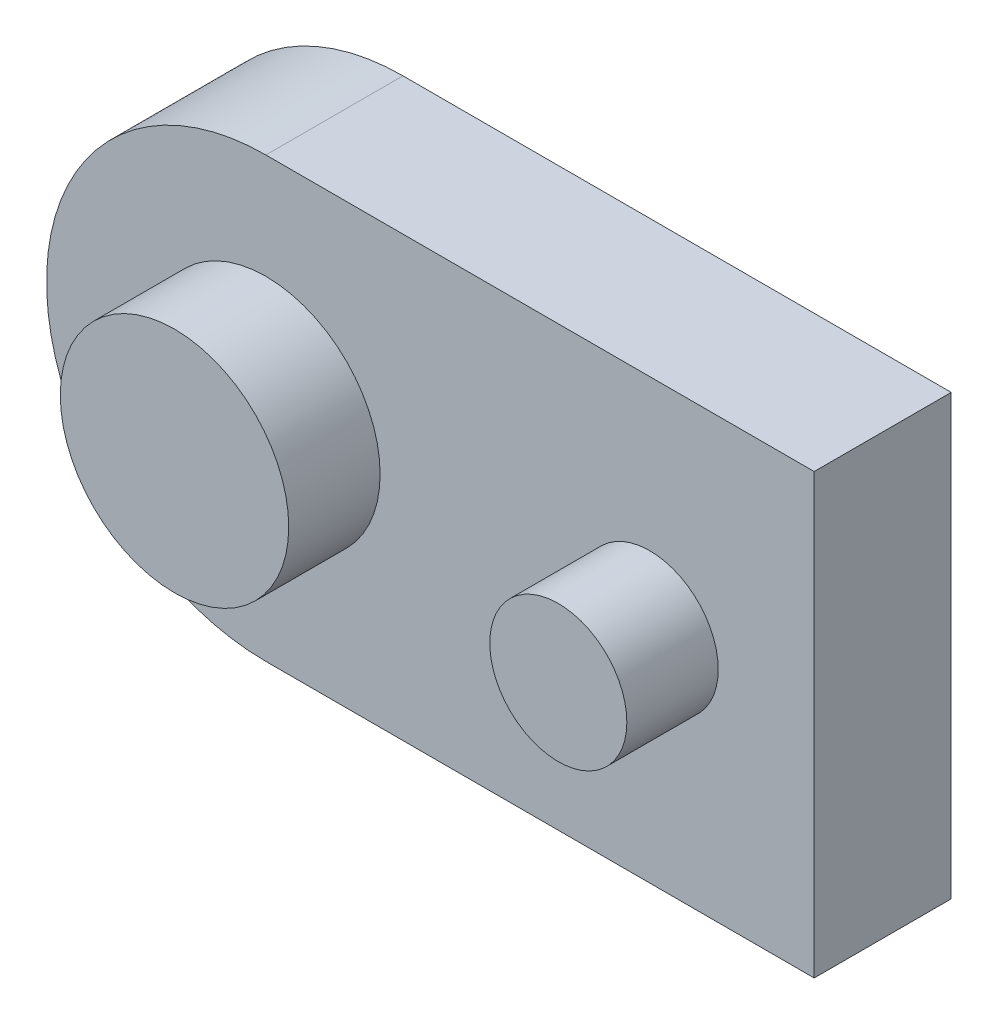
SolidWorks part; units mm, degrees
ref_plane "Front Plane" through (0, 0, 0) normal (0, 0, 1) x (1, 0, 0)
ref_plane "Top Plane" through (0, 0, 0) normal (0, 1, 0) x (1, 0, 0)
ref_plane "Right Plane" through (0, 0, 0) normal (1, 0, 0) x (0, 0, -1)
sketch "Sketch2" plane through (0, 0, 0) normal (0, 0, 1) x (1, 0, 0)
  line L1 (0, 4.8) -> (12, 4.8)
  line L2 (12, 4.8) -> (12, -4.8)
  line L3 (12, -4.8) -> (0, -4.8)
  circle A0 centre (0, 0) radius 2.5
  circle A1 centre (8.4, 0) radius 1.5
  arc A2 (0, 4.8) -> (0, -4.8) centre (0, 0) ccw
sketch "Sketch3" plane through (0, 0, 0) normal (0, 0, 1) x (1, 0, 0)
  line L0 (0, -4.8) -> (12, -4.8)
  line L1 (12, -4.8) -> (12, 4.8)
  line L2 (12, 4.8) -> (0, 4.8)
  arc A0 (0, 4.8) -> (0, -4.8) centre (0, 0) ccw
  arc A1 (0, 4.8) -> (0, -4.8) centre (0, 0) ccw construction
extrude "Boss-Extrude1" add sketch "Sketch3" along normal blind 3
extrude "Boss-Extrude2" add sketch "Sketch2" along normal blind 5 contours A1 | A0
